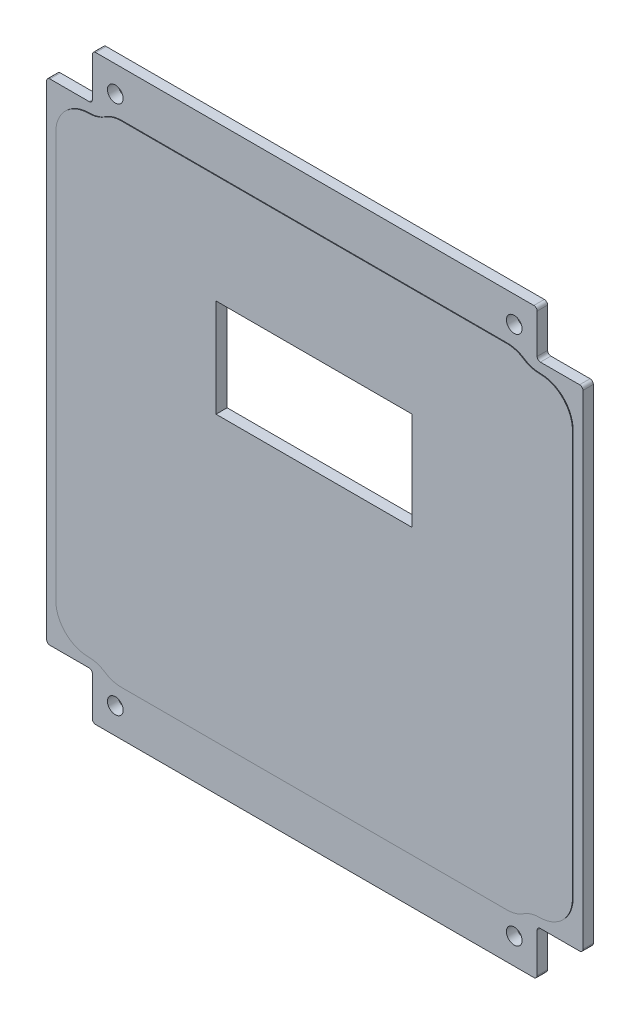
SolidWorks part; units mm, degrees
material "PET"
ref_plane "Front Plane" through (0, 0, 0) normal (0, 0, 1) x (1, 0, 0)
ref_plane "Top Plane" through (0, 0, 0) normal (0, 1, 0) x (1, 0, 0)
ref_plane "Right Plane" through (0, 0, 0) normal (1, 0, 0) x (0, 0, -1)
sketch "Sketch1" plane through (0, 0, 0) normal (0, 0, 1) x (1, 0, 0)
  line L0 (-34, 44) -> (-34, 38)
  line L1 (-33.5, -44.5) -> (33.5, -44.5)
  line L2 (-41, 37) -> (-41, -37)
  line L3 (-33.5, 44.5) -> (33.5, 44.5)
  line L4 (41, -37) -> (41, 37)
  line L5 (34, -44) -> (34, -38)
  line L6 (34.5, -37.5) -> (40.5, -37.5)
  line L7 (-34.5, 37.5) -> (-40.5, 37.5)
  line L8 (34, 44) -> (34, 38)
  line L9 (34.5, 37.5) -> (40.5, 37.5)
  line L10 (-40.5, -37.5) -> (-34.5, -37.5)
  line L11 (-34, -38) -> (-34, -44)
  line L12 (-34.5, -38) -> (34.5, 38) construction
  line L13 (34.5, -38) -> (-34.5, 38) construction
  arc A0 (-33.5, 44.5) -> (-34, 44) centre (-33.5, 44) ccw
  arc A1 (33.5, 44.5) -> (34, 44) centre (33.5, 44) cw
  arc A2 (34, 38) -> (34.5, 37.5) centre (34.5, 38) ccw
  arc A3 (40.5, 37.5) -> (41, 37) centre (40.5, 37) cw
  arc A4 (33.5, -44.5) -> (34, -44) centre (33.5, -44) ccw
  arc A5 (34.5, -37.5) -> (34, -38) centre (34.5, -38) ccw
  arc A6 (40.5, -37.5) -> (41, -37) centre (40.5, -37) ccw
  arc A7 (-34, -44) -> (-33.5, -44.5) centre (-33.5, -44) ccw
  arc A8 (-34, -38) -> (-34.5, -37.5) centre (-34.5, -38) ccw
  arc A9 (-41, -37) -> (-40.5, -37.5) centre (-40.5, -37) ccw
  arc A10 (-40.5, 37.5) -> (-41, 37) centre (-40.5, 37) ccw
  arc A11 (-34.5, 37.5) -> (-34, 38) centre (-34.5, 38) ccw
  point P0 (0, 0)
  dimension "D4" = 0.5
  dimension "D1" = 7
  dimension "D2" = 7
  dimension "D3" = 7
  dimension "D5" = 7
  dimension "D6" = 7
  dimension "D7" = 7
  dimension "D8" = 7
  dimension "D9" = 7
  dimension "D10" = 89
  dimension "D11" = 82
extrude "Boss-Extrude1" add sketch "Sketch1" along normal blind 1.6
sketch "Esboço1" plane through (0, 0, 1.6) normal (0, 0, 1) x (1, 0, 0)
  line L0 (11.8117, 0) -> (-11.978, 0) construction
  line L1 (-29.5, -37.5) -> (29.5, -37.5)
  line L2 (0, 10.1561) -> (0, -5.0161) construction
  line L3 (-29.5, 37.5) -> (29.5, 37.5)
  line L5 (-29.5, -32.5) -> (29.5, 32.5) construction
  line L6 (-29.5, 32.5) -> (29.5, -32.5) construction
  line L8 (-39.5, -31) -> (-39.5, 31)
  line L10 (39.5, -31) -> (39.5, 31)
  line L11 (-39.5, -36) -> (39.5, 36) construction
  line L12 (-39.5, 36) -> (39.5, -36) construction
  arc A0 (-34.5, 36) -> (-32, 36.75) centre (-34.5, 40.5417) ccw
  arc A1 (-29.5, 37.5) -> (-32, 36.75) centre (-29.5, 32.9583) ccw
  arc A2 (-29.5, -37.5) -> (-32, -36.75) centre (-29.5, -32.9583) cw
  arc A3 (-34.5, -36) -> (-32, -36.75) centre (-34.5, -40.5417) cw
  arc A4 (34.5, 36) -> (39.5, 31) centre (34.5, 31) cw
  arc A5 (34.5, -36) -> (39.5, -31) centre (34.5, -31) ccw
  arc A6 (-34.5, -36) -> (-39.5, -31) centre (-34.5, -31) cw
  arc A7 (-39.5, 31) -> (-34.5, 36) centre (-34.5, 31) cw
  arc A8 (29.5, -37.5) -> (32, -36.75) centre (29.5, -32.9583) ccw
  arc A9 (34.5, -36) -> (32, -36.75) centre (34.5, -40.5417) ccw
  arc A10 (29.5, 37.5) -> (32, 36.75) centre (29.5, 32.9583) cw
  arc A11 (34.5, 36) -> (32, 36.75) centre (34.5, 40.5417) cw
  point P0 (0, 0)
  point P1 (0, 0)
  dimension "D2" = 5
  dimension "D3" = 75
  dimension "D5" = 79
extrude "Boss-Extrude2" add sketch "Esboço1" along normal blind 0.1
hole_wizard "M2 Hole1-FixingStructure" positions "Sketch3" profile "Sketch2" hole size "M2" standard "DIN"
sketch "Sketch3" plane through (0, 0, 0) normal (0, 0, -1) x (-1, 0, 0)
  line L0 (-33.5, 44.5) -> (33.5, 44.5) construction
  line L1 (33.5, -44.5) -> (-33.5, -44.5) construction
  line L2 (-41, -37) -> (-41, 37) construction
  line L3 (41, 37) -> (41, -37) construction
  point P0 (-30.5, 40.5)
  point P2 (30.5, 40.5)
  point P4 (-30.5, -40.5)
  point P6 (30.5, -40.5)
  dimension "D1" = 4
  dimension "D2" = 4
  dimension "D3" = 10.5
  dimension "D4" = 10.5
sketch "Sketch2" plane through (30.5, 40.5, 0) normal (1, 0, 0) x (0, 1, 0)
  line L0 (0, 0) -> (0, 200.721)
  line L1 (0, 200.721) -> (1.2, 200)
  line L2 (1.2, 200) -> (1.2, 0)
  line L5 (1.2, 0) -> (0, 0)
  line L10 (0, 200.721) -> (-1.2, 200) construction
  line L11 (0, -6.35) -> (0, 107.95) construction
  dimension "Hole Dia." = 2.4
  dimension "Hole Depth" = 200
  dimension "Drill Angle" = 118
sketch "Sketch4" plane through (0, 0, 0) normal (0, 0, -1) x (-1, 0, 0)
  line L0 (33.5, -44.5) -> (-33.5, -44.5) construction
  line L1 (-15, 20.9) -> (15, 20.9)
  line L2 (-15, 20.9) -> (-15, 5.9)
  line L3 (-15, 5.9) -> (15, 5.9)
  line L4 (15, 20.9) -> (15, 5.9)
  line L5 (-15, 20.9) -> (15, 5.9) construction
  line L6 (-15, 5.9) -> (15, 20.9) construction
  point P0 (0, 13.4)
  dimension "D1" = 15
  dimension "D2" = 50.4
  dimension "D3" = 30
extrude "Cut-Extrude1" cut sketch "Sketch4" against normal up to surface (1.7 mm away) up to face at (0, 0, 1.7)
